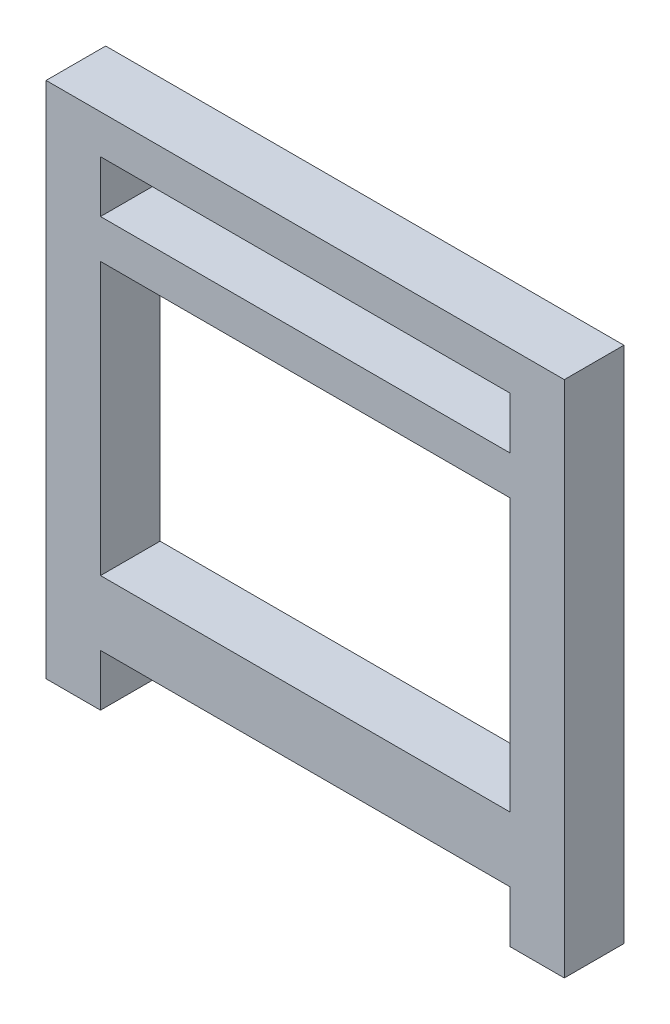
SolidWorks part; units mm, degrees
ref_plane "Front Plane" through (0, 0, 0) normal (0, 0, 1) x (1, 0, 0)
ref_plane "Top Plane" through (0, 0, 0) normal (0, 1, 0) x (1, 0, 0)
ref_plane "Right Plane" through (0, 0, 0) normal (1, 0, 0) x (0, 0, -1)
sketch "Sketch1" plane through (0, 0, 0) normal (0, 0, 1) x (1, 0, 0)
  line L0 (0, 0) -> (0, -2)
  line L1 (2.1, 0) -> (17.9, 0)
  line L2 (0, 0) -> (0, 18)
  line L3 (0, 18) -> (20, 18)
  line L4 (20, 0) -> (20, 18)
  line L5 (0, -2) -> (2.1, -2)
  line L6 (2.1, -2) -> (2.1, 0)
  line L7 (20, 0) -> (20, -2)
  line L8 (20, -2) -> (17.9, -2)
  line L9 (17.9, -2) -> (17.9, 0)
  line L10 (2.1, 0) -> (2.1, 2.5) construction
  line L12 (2.1, 2.5) -> (17.9, 2.5)
  line L13 (2.1, 2.5) -> (2.1, 13)
  line L14 (2.1, 13) -> (17.9, 13)
  line L15 (17.9, 2.5) -> (17.9, 13)
  line L16 (2.1, 14.5) -> (17.9, 14.5)
  line L17 (2.1, 14.5) -> (2.1, 16.5)
  line L18 (2.1, 16.5) -> (17.9, 16.5)
  line L19 (17.9, 14.5) -> (17.9, 16.5)
  dimension "D1" = 18
  dimension "D2" = 20
  dimension "D3" = 2.1
  dimension "D4" = 2
  dimension "D5" = 2
  dimension "D6" = 2.1
  dimension "D7" = 2.5
  dimension "D8" = 10.5
  dimension "D9" = 2
  dimension "D10" = 1.5
  dimension "D11" = 15.8
extrude "Boss-Extrude1" add sketch "Sketch1" along normal blind 2.3
